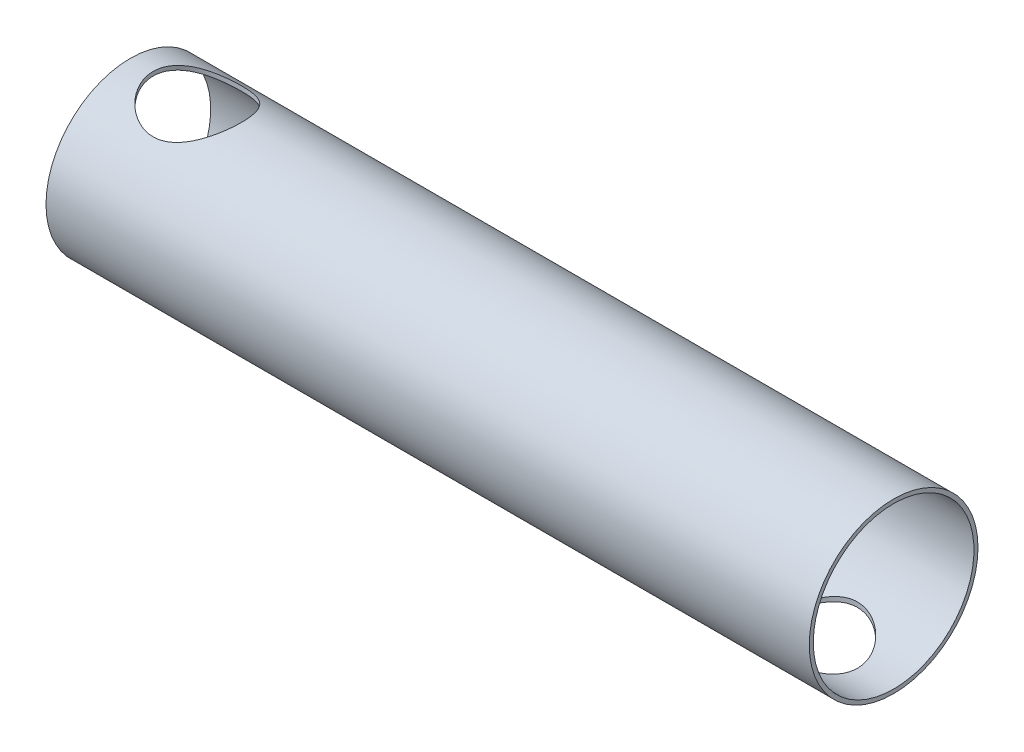
SolidWorks part; units mm, degrees
material " 12Х18Н10Т ГОСТ 4543-71"
ref_plane "Спереди" through (0, 0, 0) normal (0, 0, 1) x (1, 0, 0)
ref_plane "Сверху" through (0, 0, 0) normal (0, 1, 0) x (1, 0, 0)
ref_plane "Справа" through (0, 0, 0) normal (1, 0, 0) x (0, 0, -1)
sketch "Эскиз1" plane through (0, 0, 0) normal (0, 0, 1) x (1, 0, 0)
  line L0 (0, 0) -> (177.0443, 0) construction
  line L1 (0, -300) -> (2850, -300)
  line L2 (0, -315) -> (2850, -315)
  line L3 (0, -300) -> (0, -315)
  line L4 (2850, -300) -> (2850, -315)
  dimension "D1" = 600
  dimension "D3" = 2850
  dimension "D2" = 15
revolve "Повернуть1" add sketch "Эскиз1" angle 360 about L0
sketch "Эскиз2" plane through (0, 0, 0) normal (0, 1, 0) x (1, 0, 0)
  line L0 (0, 0) -> (3179.6435, 0) construction
  line L1 (0, 315) -> (0, -315) construction
  circle A0 centre (250, 0) radius 165
  dimension "D1" = 330
  dimension "D2" = 250
extrude "Вырез-Вытянуть1" cut sketch "Эскиз2" along normal through all
sketch "Эскиз3" plane through (0, 0, 0) normal (0, 1, 0) x (1, 0, 0)
  line L0 (0, 0) -> (2800, 0) construction
  circle A1 centre (2550, 0) radius 165
  dimension "D3" = 250
  dimension "D2" = 2800
extrude "Вырез-Вытянуть2" cut sketch "Эскиз3" against normal through all
